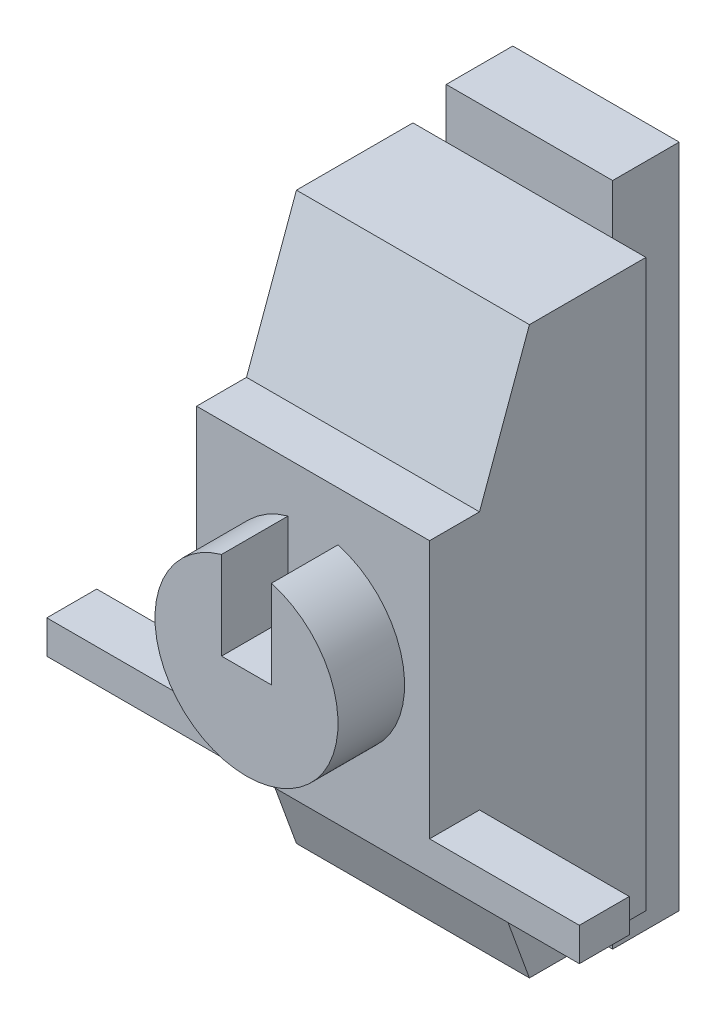
SolidWorks part; units mm, degrees
ref_plane "Спереди" through (0, 0, 0) normal (0, 0, 1) x (1, 0, 0)
ref_plane "Сверху" through (0, 0, 0) normal (0, 1, 0) x (1, 0, 0)
ref_plane "Справа" through (0, 0, 0) normal (1, 0, 0) x (0, 0, -1)
sketch "Эскиз1" plane through (0, 0, 0) normal (0, 0, 1) x (1, 0, 0)
  line L1 (-5, -20) -> (5, -20)
  line L2 (-5, -20) -> (-5, 20)
  line L3 (-5, 20) -> (5, 20)
  line L4 (5, -20) -> (5, 20)
  line L5 (-5, -20) -> (5, 20) construction
  line L6 (-5, 20) -> (5, -20) construction
  point P0 (0, 0)
  dimension "D1" = 10
  dimension "D2" = 40
extrude "Бобышка-Вытянуть1" add sketch "Эскиз1" along normal blind 4
sketch "Эскиз3" plane through (0, 0, 0) normal (1, 0, 0) x (0, 0, -1)
  line L0 (0, 0) -> (-22.9591, 0) construction
  line L1 (-17, -8.7576) -> (-17, 8.7576)
  line L2 (-17, 8.7576) -> (-14, 8.7576)
  line L3 (-14, 8.7576) -> (-11, 17)
  line L4 (-11, 17) -> (-4, 17)
  line L5 (-4, -20) -> (-4, 20) construction
  line L6 (-4, 17) -> (-4, -17)
  line L7 (-11, -17) -> (-4, -17)
  line L8 (-14, -8.7576) -> (-11, -17)
  line L9 (-17, -8.7576) -> (-14, -8.7576)
  point P12 (-4, 0)
  point P15 (-17, 0)
  dimension "D1" = 17
  dimension "D2" = 7
  dimension "D3" = 70
  dimension "D4" = 3
  dimension "D5" = 13
extrude "Бобышка-Вытянуть2" add sketch "Эскиз3" against normal blind 7 and the other way blind 7
sketch "Эскиз4" plane through (0, -8.7576, 0) normal (0, -1, 0) x (1, 0, 0)
  line L0 (0, 17) -> (0, 14) construction
  line L1 (7, 17) -> (-7, 17) construction
  line L2 (7, 14) -> (-7, 14) construction
  line L4 (-16, 14) -> (16, 14)
  line L5 (-16, 14) -> (-16, 17)
  line L6 (-16, 17) -> (16, 17)
  line L7 (16, 14) -> (16, 17)
  line L8 (-16, 14) -> (16, 17) construction
  line L9 (-16, 17) -> (16, 14) construction
  point P6 (0, 15.5)
  dimension "D1" = 32
extrude "Бобышка-Вытянуть3" add sketch "Эскиз4" against normal blind 2
sketch "Эскиз5" plane through (0, 0, 17) normal (0, 0, 1) x (1, 0, 0)
  circle A0 centre (0, 0.5) radius 5.5
  dimension "D1" = 11
  dimension "D2" = 0.5
extrude "Бобышка-Вытянуть4" add sketch "Эскиз5" along normal blind 4
sketch "Эскиз6" plane through (0, 0, 21) normal (0, 0, 1) x (1, 0, 0)
  line L0 (0, 0) -> (0, 8.7576) construction
  line L1 (7, 8.7576) -> (-7, 8.7576) construction
  line L3 (-1.5, 0.5) -> (1.5, 0.5)
  line L4 (-1.5, 0.5) -> (-1.5, 6)
  line L5 (-1.5, 6) -> (1.5, 6)
  line L6 (1.5, 0.5) -> (1.5, 6)
  line L7 (-1.5, 0.5) -> (1.5, 6) construction
  line L8 (-1.5, 6) -> (1.5, 0.5) construction
  circle A0 centre (0, 0.5) radius 5.5 construction
  point P5 (0, 3.25)
  point P12 (0, 0.5)
  dimension "D1" = 3
extrude "Вырез-Вытянуть1" cut sketch "Эскиз6" against normal up to surface (4 mm away) up to face at (0, -3.3788, 17)
